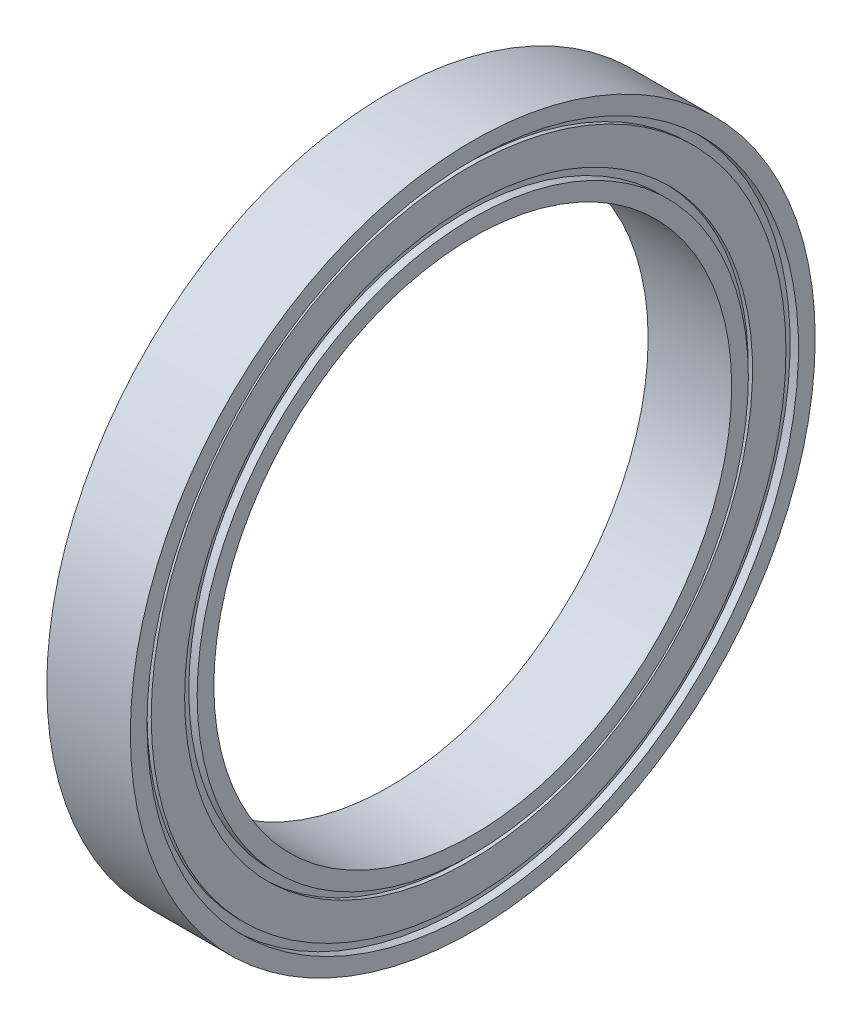
SolidWorks part; units mm, degrees
ref_plane "Front Plane" through (0, 0, 0) normal (0, 0, 1) x (1, 0, 0)
ref_plane "Top Plane" through (0, 0, 0) normal (0, 1, 0) x (1, 0, 0)
ref_plane "Right Plane" through (0, 0, 0) normal (1, 0, 0) x (0, 0, -1)
sketch "Sketch1" plane through (0, 0, 0) normal (0, 0, 1) x (1, 0, 0)
  line L0 (0, 0) -> (0, 31) construction
  line L1 (0, 31) -> (0, 41) construction
  line L2 (-5, 41) -> (5, 41)
  line L3 (5, 41) -> (5, 39)
  line L4 (5, 39) -> (4, 39)
  line L5 (4, 39) -> (4, 38)
  line L6 (4, 38) -> (4.5, 38)
  line L7 (4.5, 38) -> (4.5, 34)
  line L8 (4.5, 36) -> (0, 36) construction
  line L9 (4, 34) -> (4.5, 34)
  line L10 (4, 33) -> (4, 34)
  line L11 (5, 33) -> (4, 33)
  line L12 (5, 31) -> (5, 33)
  line L13 (-5, 31) -> (5, 31)
  line L14 (-5, 31) -> (-5, 33)
  line L15 (-5, 33) -> (-4, 33)
  line L16 (-4, 33) -> (-4, 34)
  line L17 (-4, 34) -> (-4.5, 34)
  line L18 (-4.5, 38) -> (-4.5, 34)
  line L19 (-4, 38) -> (-4.5, 38)
  line L20 (-4, 39) -> (-4, 38)
  line L21 (-5, 39) -> (-4, 39)
  line L22 (-5, 41) -> (-5, 39)
  line L23 (0, 0) -> (13.2088, 0) construction
  dimension "D1" = 5
  dimension "D2" = 5
  dimension "D3" = 4
  dimension "D4" = 4.5
  dimension "D5" = 2
  dimension "D6" = 2
  dimension "D7" = 36
  dimension "D8" = 0.5
revolve "Revolve1" add sketch "Sketch1" angle 360 about L23
